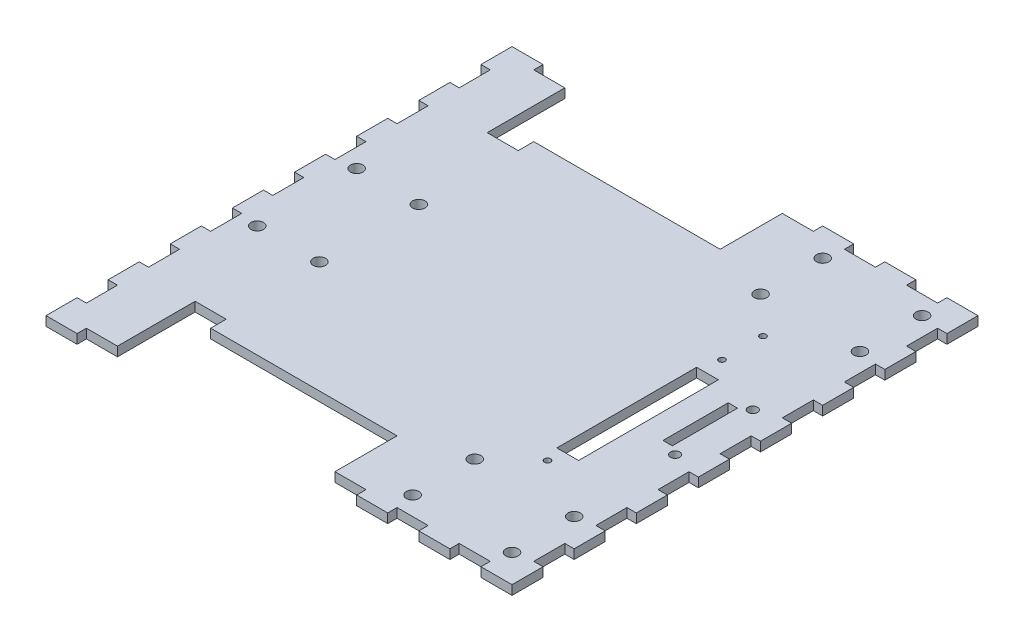
SolidWorks part; units mm, degrees
ref_plane "Alzado" through (0, 0, 0) normal (0, 0, 1) x (1, 0, 0)
ref_plane "Planta" through (0, 0, 0) normal (0, 1, 0) x (1, 0, 0)
ref_plane "Vista lateral" through (0, 0, 0) normal (1, 0, 0) x (0, 0, -1)
sketch "Croquis1" plane through (0, 0, 0) normal (0, 1, 0) x (1, 0, 0)
  line L0 (-75, -75) -> (-75, -65)
  line L1 (-75, -75) -> (-65, -75)
  line L2 (-75, 75) -> (-65, 75)
  line L3 (75, -75) -> (75, -65)
  line L4 (-75, -75) -> (75, 75) construction
  line L5 (-75, 75) -> (75, -75) construction
  line L6 (0, 0) -> (0, 41.1492) construction
  line L7 (0, 0) -> (52.6903, 0) construction
  line L10 (-65, 75) -> (-65, 72)
  line L27 (25, 75) -> (25, 72)
  line L29 (35, 75) -> (35, 72)
  line L30 (35, 72) -> (45, 72)
  line L31 (45, 75) -> (45, 72)
  line L33 (55, 75) -> (55, 72)
  line L34 (55, 72) -> (65, 72)
  line L35 (65, 75) -> (65, 72)
  line L36 (-65, 72) -> (-55, 72)
  line L37 (65, -75) -> (65, -72)
  line L38 (55, -72) -> (65, -72)
  line L39 (55, -75) -> (55, -72)
  line L41 (45, -75) -> (45, -72)
  line L42 (35, -72) -> (45, -72)
  line L43 (35, -75) -> (35, -72)
  line L45 (25, -75) -> (25, -72)
  line L46 (15, -72) -> (25, -72)
  line L61 (-65, -72) -> (-55, -72)
  line L62 (-65, -75) -> (-65, -72)
  line L65 (-75, 45) -> (-72, 45)
  line L66 (-75, 65) -> (-72, 65)
  line L68 (-75, 55) -> (-72, 55)
  line L69 (-72, 65) -> (-72, 55)
  line L71 (-75, 35) -> (-72, 35)
  line L72 (-72, 45) -> (-72, 35)
  line L73 (-75, 25) -> (-72, 25)
  line L75 (-75, 15) -> (-72, 15)
  line L76 (-72, 25) -> (-72, 15)
  line L77 (-75, 5) -> (-72, 5)
  line L79 (-75, -5) -> (-72, -5)
  line L80 (-72, 5) -> (-72, -5)
  line L81 (-75, -15) -> (-72, -15)
  line L83 (-75, -25) -> (-72, -25)
  line L84 (-72, -15) -> (-72, -25)
  line L85 (-75, -35) -> (-72, -35)
  line L87 (-75, -45) -> (-72, -45)
  line L88 (-72, -35) -> (-72, -45)
  line L89 (-75, -55) -> (-72, -55)
  line L91 (-75, -65) -> (-72, -65)
  line L92 (-72, -55) -> (-72, -65)
  line L93 (-75, 55) -> (-75, 45) construction
  line L94 (72, 45) -> (72, 35)
  line L95 (75, 35) -> (72, 35)
  line L97 (72, 65) -> (72, 55)
  line L98 (75, 55) -> (72, 55)
  line L100 (75, 65) -> (72, 65)
  line L101 (75, 45) -> (72, 45)
  line L102 (72, -55) -> (72, -65)
  line L103 (75, -65) -> (72, -65)
  line L105 (75, -55) -> (72, -55)
  line L106 (72, -35) -> (72, -45)
  line L107 (75, -45) -> (72, -45)
  line L109 (75, -35) -> (72, -35)
  line L114 (25, -75) -> (35, -75)
  line L115 (45, -75) -> (55, -75)
  line L116 (65, -75) -> (75, -75)
  line L117 (75, -55) -> (75, -45)
  line L118 (75, -35) -> (75, -25)
  line L119 (75, 45) -> (75, 55)
  line L120 (75, 65) -> (75, 75)
  line L121 (59.1, -10.5) -> (59.1, -7.5)
  line L122 (65, 75) -> (75, 75)
  line L123 (45, 75) -> (55, 75)
  line L124 (59.1, -10.5) -> (62.1, -10.5)
  line L125 (25, 75) -> (35, 75)
  line L126 (59.1, 10.5) -> (62.1, 10.5)
  line L128 (62.1, -10.5) -> (62.1, 10.5)
  line L129 (59.1, -10.5) -> (62.1, 10.5) construction
  line L131 (59.1, 10.5) -> (62.1, -10.5) construction
  line L134 (-75, 65) -> (-75, 75)
  line L135 (-75, 45) -> (-75, 55)
  line L136 (-75, 25) -> (-75, 35)
  line L137 (-75, 5) -> (-75, 15)
  line L138 (-75, -15) -> (-75, -5)
  line L139 (-75, -35) -> (-75, -25)
  line L140 (-75, -55) -> (-75, -45)
  line L171 (15, 72) -> (15, 52)
  line L172 (-45, 75) -> (-45, 72) [skipped]
  line L174 (-25, 75) -> (-25, 72) [skipped]
  line L176 (-5, 75) -> (-5, 72) [skipped]
  line L178 (15, 75) -> (15, 72) [skipped]
  line L179 (15, -72) -> (15, -52)
  line L180 (15, 72) -> (25, 72)
  line L188 (59.1, 7.5) -> (59.1, 10.5)
  line L198 (75, -25) -> (72, -25)
  line L200 (75, -15) -> (72, -15)
  line L201 (72, -25) -> (72, -15)
  line L202 (75, -5) -> (72, -5)
  line L203 (72, -5) -> (72, 5)
  line L204 (75, 5) -> (72, 5)
  line L206 (75, 15) -> (72, 15)
  line L207 (72, 15) -> (72, 25)
  line L208 (75, 25) -> (72, 25)
  line L209 (75, -15) -> (75, -5)
  line L210 (75, 5) -> (75, 15)
  line L211 (75, 25) -> (75, 35)
  line L212 (59.1, 7.5) -> (59.1, -7.5)
  line L214 (51.1, -29.675) -> (44.1, -29.675)
  line L215 (51.1, -29.675) -> (51.1, 15.325)
  line L216 (51.1, 15.325) -> (44.1, 15.325)
  line L217 (44.1, -29.675) -> (44.1, 15.325)
  line L221 (-55, 47) -> (-45, 47)
  line L222 (-45, 52) -> (-45, 47)
  line L223 (-55, -47) -> (-45, -47)
  line L224 (-45, -52) -> (-45, -47)
  line L227 (-45, 52) -> (15, 52)
  line L228 (-45, -52) -> (15, -52)
  line L229 (-55, 72) -> (-55, 47)
  line L231 (-55, -72) -> (-55, -47)
  circle A0 centre (65, 12.5) radius 1.5
  circle A1 centre (65, -12.5) radius 1.5
  circle A2 centre (66, 66) radius 2
  circle A3 centre (34, 66) radius 2
  circle A4 centre (66, 46) radius 2
  circle A5 centre (34, 46) radius 2
  circle A6 centre (66, -46) radius 2
  circle A7 centre (34, -46) radius 2
  circle A8 centre (66, -66) radius 2
  circle A9 centre (34, -66) radius 2
  circle A10 centre (-66, 16) radius 2
  circle A11 centre (-66, -16) radius 2
  circle A12 centre (-46, 16) radius 2
  circle A13 centre (-46, -16) radius 2
  circle A15 centre (46.1, 34.675) radius 1
  circle A16 centre (46.1, -34.675) radius 1
  circle A17 centre (46.1, 21.475) radius 1
  point P1 (0, 0)
  point P15 (65, 73.5)
  point P39 (60.6, 0)
  point P138 (73.5, 25)
  point P156 (35.85, 0)
  dimension "D25" = 12.5
  dimension "D13" = 3
  dimension "D23" = 4
  dimension "D28" = 6
  dimension "D30" = 70
  dimension "D31" = 4
  dimension "D37" = 2
  dimension "D48" = 2
  dimension "D1" = 150
  dimension "D2" = 150
  dimension "D3" = 10
  dimension "D4" = 10
  dimension "D5" = 3
  dimension "D7" = 10
  dimension "D8" = 10
  dimension "D9" = 3
  dimension "D10" = 10
  dimension "D12" = 20
  dimension "D14" = 3
  dimension "D15" = 21
  dimension "D16" = 5.9
  dimension "D17" = 20
  dimension "D19" = 15
  dimension "D20" = 10
  dimension "D21" = 10
  dimension "D22" = 10
  dimension "D24" = 20
  dimension "D26" = 10
  dimension "D27" = 32
  dimension "D32" = 32
  dimension "D33" = 20
  dimension "D34" = 6
  dimension "D36" = 13
  dimension "D29" = 6
  dimension "D35" = 16
  dimension "D38" = 69.35
  dimension "D39" = 45
  dimension "D40" = 7
  dimension "D41" = 5
  dimension "D42" = 10
  dimension "D43" = 10
  dimension "D44" = 3
  dimension "D45" = 3
  dimension "D46" = 10
  dimension "D47" = 15
  dimension "D49" = 13.2
  dimension "D50" = 10
  dimension "D51" = 5
  dimension "D52" = 70
  dimension "D6" = 7
  dimension "D11" = 7
extrude "Saliente-Extruir2" add sketch "Croquis1" along normal blind 3
